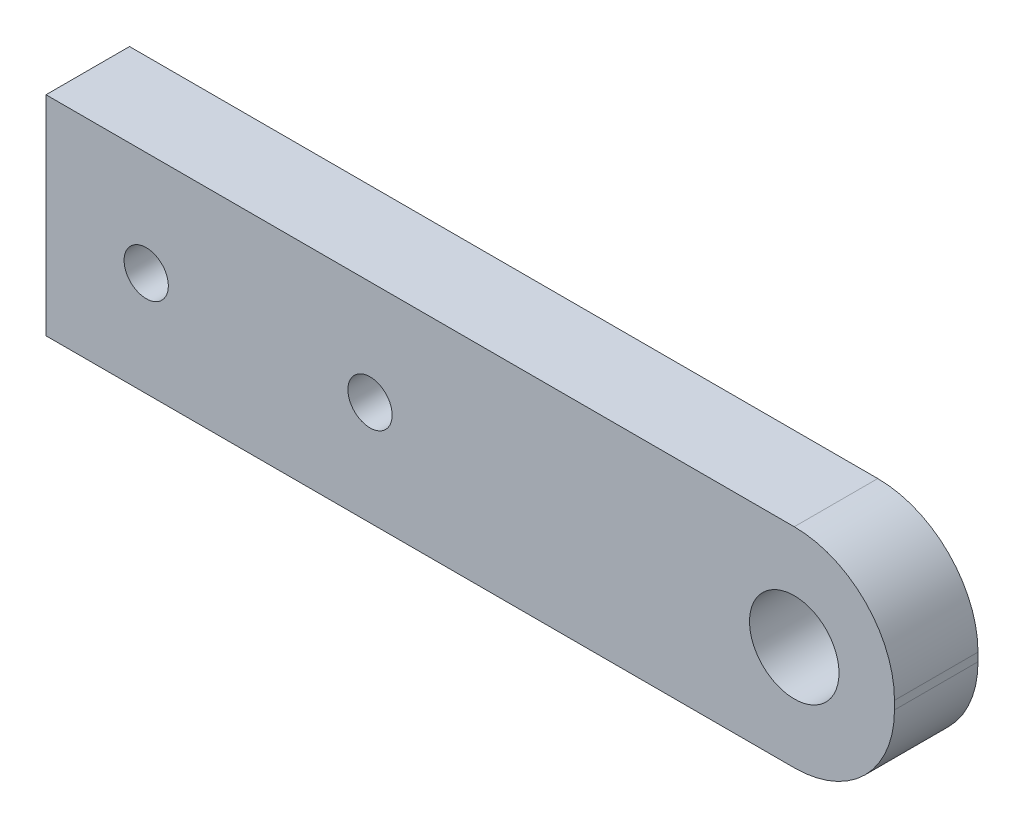
SolidWorks part; units mm, degrees
ref_plane "Front" through (0, 0, 0) normal (0, 0, 1) x (1, 0, 0)
ref_plane "Top" through (0, 0, 0) normal (0, 1, 0) x (1, 0, 0)
ref_plane "Right" through (0, 0, 0) normal (1, 0, 0) x (0, 0, -1)
sketch "Sketch1" plane through (0, 0, 0) normal (0, 0, 1) x (1, 0, 0)
  line L0 (0, 0) -> (127, 0) construction
  line L2 (114.3, 12.5) -> (12.7, 12.5)
  line L3 (114.3, 12.5) -> (114.3, -12.5)
  line L4 (114.3, -12.5) -> (12.7, -12.5)
  line L5 (12.7, 12.5) -> (12.7, -12.5)
  line L6 (114.3, 12.5) -> (12.7, -12.5) construction
  line L7 (114.3, -12.5) -> (12.7, 12.5) construction
  circle A0 centre (102.3, 0) radius 5.3578
  circle A1 centre (24.7, 0) radius 2.65
  circle A2 centre (51.5, 0) radius 2.65
  point P3 (63.5, 0)
  dimension "D4" = 10.7156
  dimension "D5" = 5.3
  dimension "D1" = 101.6
  dimension "D2" = 25
  dimension "D3" = 12
  dimension "D6" = 12
  dimension "D7" = 50.8
extrude "Boss-Extrude1" add sketch "Sketch1" along normal blind 10
fillet "Fillet1" radius 12 2 edges at (114.3, -12.5, 5) (114.3, 12.5, 5)
